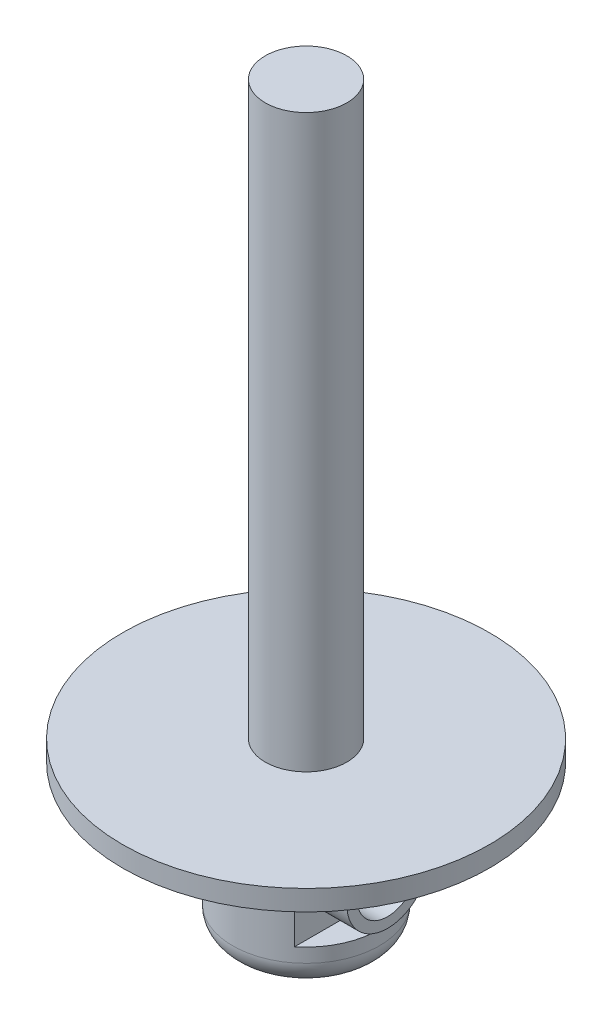
SolidWorks part; units mm, degrees
ref_plane "Front Plane" through (0, 0, 0) normal (0, 0, 1) x (1, 0, 0)
ref_plane "Top Plane" through (0, 0, 0) normal (0, 1, 0) x (1, 0, 0)
ref_plane "Right Plane" through (0, 0, 0) normal (1, 0, 0) x (0, 0, -1)
sketch "Sketch1" plane through (0, 0, 0) normal (0, 1, 0) x (1, 0, 0)
  circle A0 centre (0, 0) radius 45
  dimension "D1" = 90
extrude "Boss-Extrude1" add sketch "Sketch1" along normal blind 5
sketch "Sketch2" plane through (0, 5, 0) normal (0, 1, 0) x (1, 0, 0)
  circle A0 centre (0, 0) radius 10
  dimension "D1" = 20
extrude "Boss-Extrude2" add sketch "Sketch2" along normal blind 140
sketch "Sketch3" plane through (0, 0, 0) normal (0, -1, 0) x (1, 0, 0)
  circle A0 centre (0, 0) radius 18
  dimension "D1" = 36
extrude "Boss-Extrude3" add sketch "Sketch3" along normal blind 36
fillet "Fillet1" radius 6 1 edges at (0, -36, -18)
sketch "Sketch4" plane through (0, 0, 0) normal (0, 0, 1) x (1, 0, 0)
  line L0 (0, 0) -> (0, -36) construction
  line L1 (-12, -36) -> (12, -36) construction
  line L2 (11.25, -26.5464) -> (32.8988, -26.5464)
  line L3 (32.8988, -26.5464) -> (32.8988, -4.0464)
  line L4 (32.8988, -4.0464) -> (11.25, -4.0464)
  line L5 (11.25, -4.0464) -> (11.25, -26.5464)
  line L6 (-11.25, -4.0464) -> (-11.25, -26.5464)
  line L7 (-32.8988, -4.0464) -> (-11.25, -4.0464)
  line L8 (-32.8988, -26.5464) -> (-32.8988, -4.0464)
  line L9 (-11.25, -26.5464) -> (-32.8988, -26.5464)
  dimension "D1" = 22.5
  dimension "D2" = 22.5
extrude "Cut-Extrude1" cut sketch "Sketch4" against normal through all both and the other way through all
sketch "Sketch5" plane through (11.25, 0, 0) normal (1, 0, 0) x (0, 0, -1)
  circle A0 centre (0, -15.2964) radius 7.5
  dimension "D1" = 15
extrude "Cut-Extrude2" cut sketch "Sketch5" against normal through all
sketch "Sketch7" plane through (0, 0, 0) normal (1, 0, 0) x (0, 0, -1)
  circle A0 centre (0, -15.2964) radius 10
  circle A1 centre (0, -15.2964) radius 7.5 construction
  circle A2 centre (0, -15.2964) radius 7.5
  dimension "D1" = 20
extrude "Boss-Extrude4" add sketch "Sketch7" along normal mid plane 40
